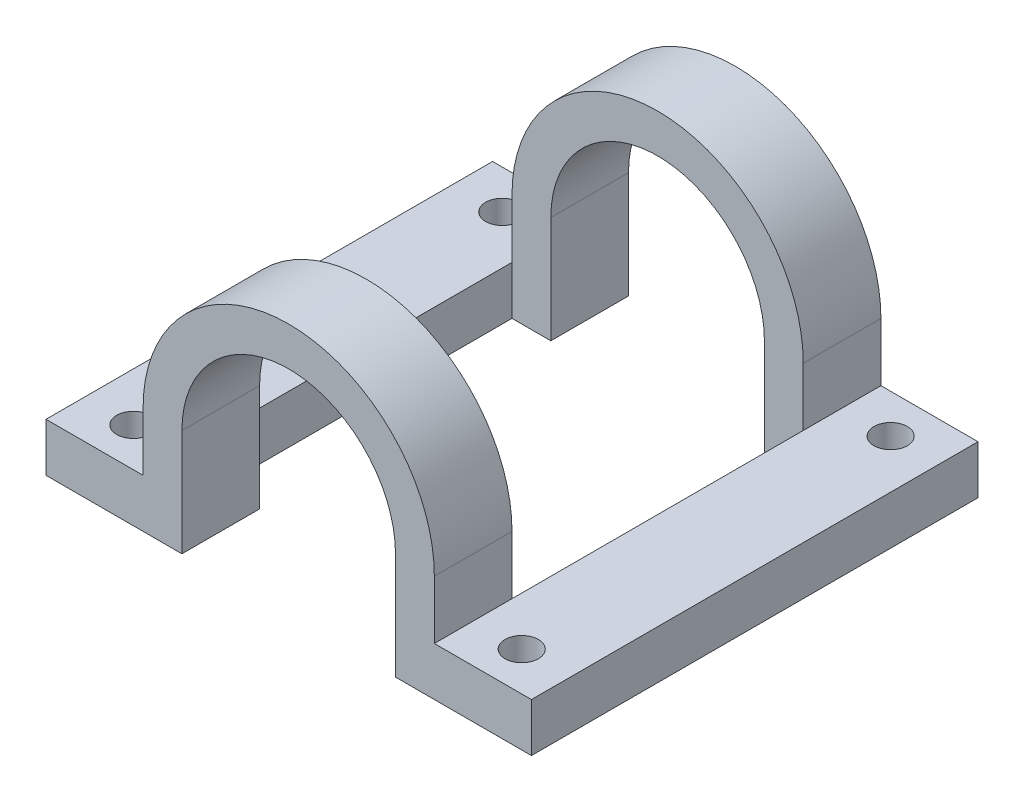
SolidWorks part; units mm, degrees
ref_plane "Front Plane" through (0, 0, 0) normal (0, 0, 1) x (1, 0, 0)
ref_plane "Top Plane" through (0, 0, 0) normal (0, 1, 0) x (1, 0, 0)
ref_plane "Right Plane" through (0, 0, 0) normal (1, 0, 0) x (0, 0, -1)
sketch "Sketch1" plane through (0, 0, 0) normal (0, 0, 1) x (1, 0, 0)
  line L0 (0, 0) -> (0, 6.35)
  line L1 (0, 6.35) -> (12.7, 6.35)
  line L2 (50.8, 6.35) -> (63.5, 6.35)
  line L4 (17.78, 13.97) -> (45.72, 13.97) construction
  line L5 (0, 0) -> (17.78, 0)
  line L6 (63.5, 0) -> (63.5, 6.35)
  line L9 (12.7, 13.97) -> (12.7, 6.35)
  line L10 (50.8, 13.97) -> (50.8, 6.35)
  line L13 (45.72, 0) -> (63.5, 0)
  line L14 (17.78, 13.97) -> (17.78, 0)
  line L15 (45.72, 13.97) -> (45.72, 0)
  arc A0 (45.72, 13.97) -> (17.78, 13.97) centre (31.75, 13.97) ccw
  arc A2 (50.8, 13.97) -> (12.7, 13.97) centre (31.75, 13.97) ccw
  dimension "D3" = 13.97
  dimension "D4" = 19.05
  dimension "D5" = 17.78
  dimension "D1" = 13.97
  dimension "D2" = 6.35
extrude "Boss-Extrude1" add sketch "Sketch1" along normal blind 10.16
sketch "Sketch2" plane through (0, 6.35, 0) normal (0, 1, 0) x (1, 0, 0)
  line L0 (12.7, -10.16) -> (12.7, 0) construction
  line L1 (12.7, -10.16) -> (0, -10.16) construction
  line L2 (31.75, 0) -> (31.75, -10.16) construction
  line L3 (50.8, 0) -> (12.7, 0) construction
  line L4 (12.7, -10.16) -> (50.8, -10.16) construction
  circle A0 centre (6.35, -5.08) radius 2.1828
  circle A1 centre (57.15, -5.08) radius 2.1828
  dimension "D3" = 4.3656
  dimension "D1" = 6.35
  dimension "D2" = 5.08
extrude "Cut-Extrude1" cut sketch "Sketch2" against normal blind 7.62
sketch "Sketch3" plane through (0, 0, 0) normal (0, 1, 0) x (1, 0, 0)
  line L0 (0, -10.16) -> (0, -29.21)
  line L1 (0, -29.21) -> (12.7, -29.21)
  line L2 (12.7, -10.16) -> (12.7, -29.21)
  line L3 (50.8, -10.16) -> (50.8, -29.21)
  line L4 (50.8, -29.21) -> (63.5, -29.21)
  line L5 (63.5, -10.16) -> (63.5, -29.21)
  line L6 (0, -10.16) -> (12.7, -10.16)
  line L7 (50.8, -10.16) -> (63.5, -10.16)
  dimension "D1" = 19.05
extrude "Boss-Extrude2" add sketch "Sketch3" along normal up to surface (6.35 mm away) up to face at (6.35, 6.35, 7.2628)
ref_plane "Plane1" through (0, 0, 29.21) normal (0, 0, 1) x (1, 0, 0)
mirror "Mirror1" about plane through (0, 0, 29.21) normal (0, 0, 1) of bodies 103
